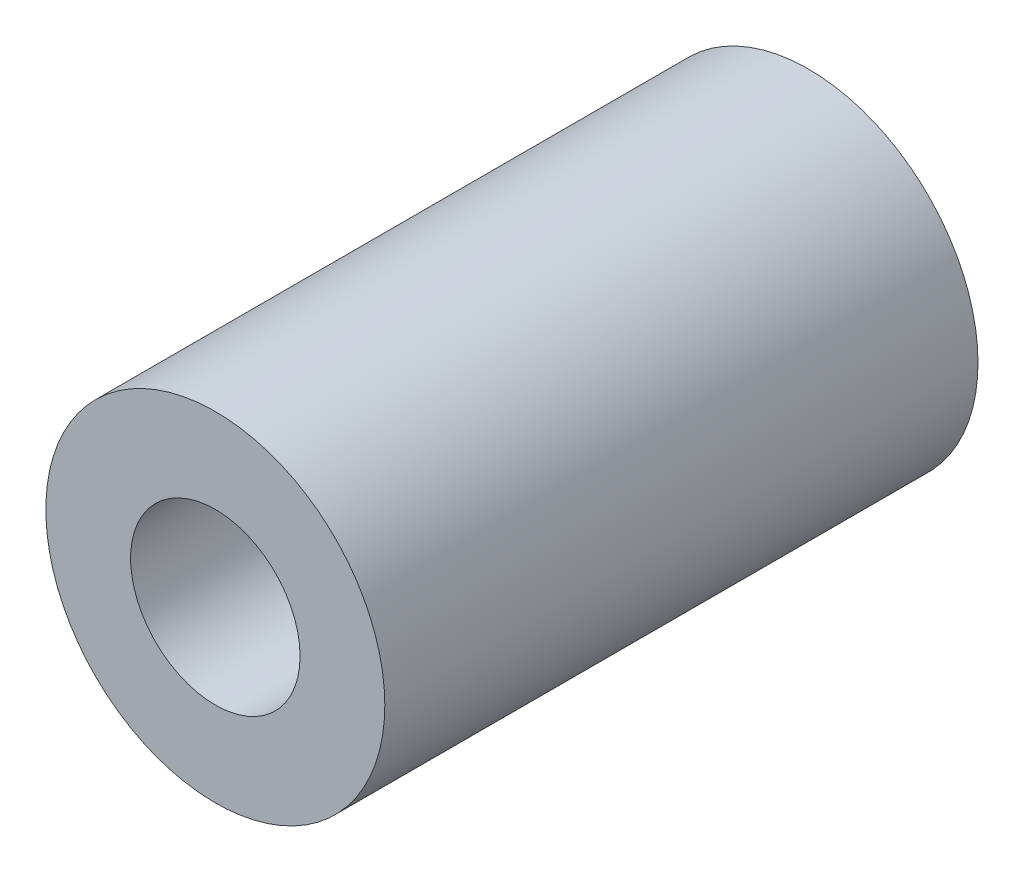
SolidWorks part; units mm, degrees
other "Bearing_3-1-1"
material "PTFE (general)"
ref_plane "Front" through (0, 0, 0) normal (0, 0, 1) x (1, 0, 0)
ref_plane "Top" through (0, 0, 0) normal (0, 1, 0) x (1, 0, 0)
ref_plane "Right" through (0, 0, 0) normal (1, 0, 0) x (0, 0, -1)
sketch "BearingSke" plane through (0, 0, 0) normal (0, 0, 1) x (1, 0, 0)
  circle A0 centre (0, 0) radius 1
  circle A1 centre (0, 0) radius 0.5
  dimension "D1" = 2
  dimension "D2" = 1
extrude "Bearing" add sketch "BearingSke" along normal blind 3.5
